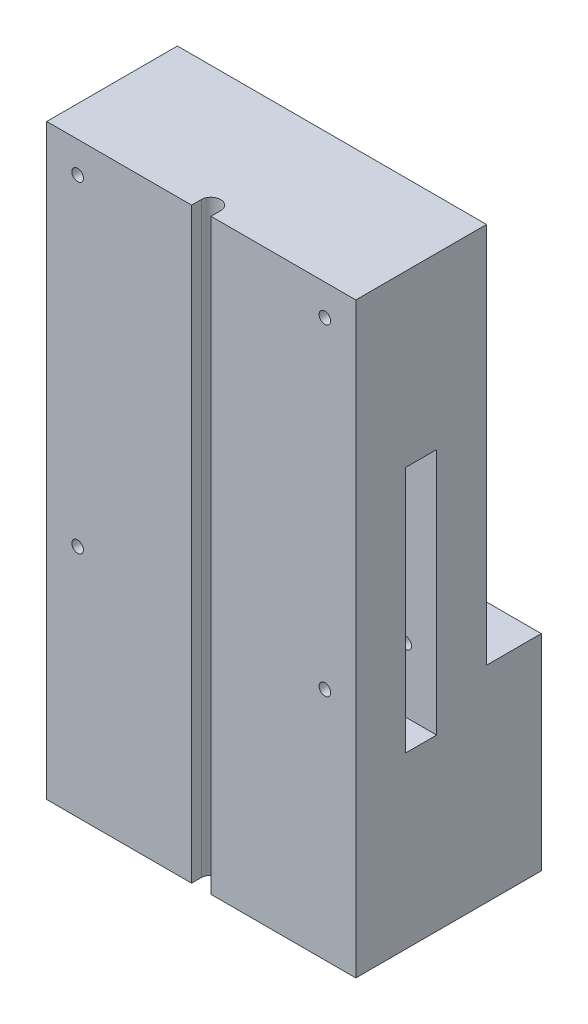
SolidWorks part; units mm, degrees
ref_plane "Front Plane" through (0, 0, 0) normal (0, 0, 1) x (1, 0, 0)
ref_plane "Top Plane" through (0, 0, 0) normal (0, 1, 0) x (1, 0, 0)
ref_plane "Right Plane" through (0, 0, 0) normal (1, 0, 0) x (0, 0, -1)
sketch "Sketch1" plane through (0, 0, 0) normal (0, 0, 1) x (1, 0, 0)
  line L1 (63.5, -120.65) -> (-63.5, -120.65)
  line L2 (63.5, -120.65) -> (63.5, 120.65)
  line L3 (63.5, 120.65) -> (-63.5, 120.65)
  line L4 (-63.5, -120.65) -> (-63.5, 120.65)
  line L5 (63.5, -120.65) -> (-63.5, 120.65) construction
  line L6 (63.5, 120.65) -> (-63.5, -120.65) construction
  point P0 (0, 0)
  dimension "D1" = 241.3
  dimension "D2" = 127
extrude "Boss-Extrude1" add sketch "Sketch1" along normal mid plane 76.2
sketch "Sketch2" plane through (0, 120.65, 0) normal (0, 1, 0) x (1, 0, 0)
  line L0 (-3.9688, -38.1) -> (-3.9688, -34.1313)
  line L1 (63.5, -38.1) -> (-63.5, -38.1) construction
  line L2 (3.9688, -38.1) -> (3.9688, -34.1313)
  line L3 (-3.9688, -34.1313) -> (0, -34.1313) construction
  line L4 (-3.9688, -38.1) -> (3.9688, -38.1)
  arc A0 (-3.9688, -34.1313) -> (3.9688, -34.1313) centre (0, -34.1313) cw
  dimension "D1" = 7.9375
extrude "Cut-Extrude1" cut sketch "Sketch2" against normal up to next contours A0 L2 L4 L0
sketch "Sketch3" plane through (0, 0, -38.1) normal (0, 0, -1) x (-1, 0, 0)
  line L0 (-22.9598, 76.2) -> (-35.7091, 76.2) construction
  line L2 (2.3909, 76.2) -> (-16.5941, 76.2) construction
  line L3 (2.3909, 31.75) -> (2.3909, 76.2) construction
  line L4 (-0.7841, 3.81) -> (-0.7841, 31.75) construction
  line L5 (-15.2621, 3.81) -> (-15.2621, 31.75) construction
  line L6 (-25.5491, 3.81) -> (-25.5491, 31.75) construction
  line L7 (-35.7091, 3.81) -> (-35.7091, 31.75) construction
  line L8 (-35.7091, 39.878) -> (-35.7091, 31.75) construction
  line L9 (-0.7841, 3.81) -> (-15.2621, 3.81) construction
  line L10 (-25.5491, 3.81) -> (-35.7091, 3.81) construction
  line L11 (-35.7091, 31.75) -> (2.3909, 31.75) construction
  line L12 (-35.7091, 76.2) -> (-35.7091, 57.8612) construction
  line L13 (-35.7091, 57.8612) -> (-35.7091, 39.878) construction
  line L14 (-23.7711, 94.234) -> (-23.7711, 76.2) construction
  line L15 (-15.7828, 76.2) -> (-15.7828, 94.234) construction
  line L16 (-42.7769, 94.234) -> (12.2231, 94.234) construction
  line L17 (21.4409, 3.81) -> (21.4409, 81.026) construction
  line L18 (21.4409, 81.026) -> (42.7769, 81.026) construction
  line L19 (42.7769, 3.81) -> (42.7769, 81.026) construction
  line L20 (21.4409, 3.81) -> (42.7769, 3.81) construction
  line L21 (-23.7711, 76.2) -> (-35.7091, 76.2) construction
  line L22 (-37.6141, 78.105) -> (-37.6141, 57.8612)
  line L23 (2.3909, 76.2) -> (-15.7828, 76.2) construction
  line L24 (2.3909, 31.75) -> (2.3909, 76.2) construction
  line L25 (-0.7841, 3.81) -> (-0.7841, 31.75) construction
  line L26 (-15.2621, 3.81) -> (-15.2621, 31.75) construction
  line L27 (-25.5491, 3.81) -> (-25.5491, 31.75) construction
  line L28 (-35.7091, 3.81) -> (-35.7091, 31.75) construction
  line L29 (-35.7091, 39.878) -> (-35.7091, 31.75) construction
  line L30 (-0.7841, 3.81) -> (-15.2621, 3.81) construction
  line L31 (-25.5491, 3.81) -> (-35.7091, 3.81) construction
  line L32 (-25.5491, 31.75) -> (-15.2621, 31.75) construction
  line L33 (-35.7091, 76.2) -> (-35.7091, 57.8612) construction
  line L34 (-35.7091, 57.8612) -> (-35.7091, 39.878) construction
  line L35 (-23.7711, 94.234) -> (-23.7711, 76.2) construction
  line L36 (-15.7828, 76.2) -> (-15.7828, 94.234) construction
  line L37 (-23.7711, 94.234) -> (-15.7828, 94.234) construction
  line L38 (21.4409, 3.81) -> (21.4409, 81.026) construction
  line L39 (21.4409, 81.026) -> (42.7769, 81.026) construction
  line L40 (42.7769, 3.81) -> (42.7769, 81.026) construction
  line L41 (21.4409, 3.81) -> (42.7769, 3.81) construction
  line L42 (-0.7841, 31.75) -> (2.3909, 31.75) construction
  line L43 (-37.6141, 57.8612) -> (-37.6141, 39.878)
  line L44 (-37.6141, 39.878) -> (-37.6141, 31.75)
  line L45 (-37.6141, 1.905) -> (-37.6141, 31.75)
  line L46 (-23.6441, 1.905) -> (-37.6141, 1.905)
  line L47 (-23.6441, 1.905) -> (-23.6441, 29.845)
  line L48 (-23.6441, 29.845) -> (-17.1671, 29.845)
  line L49 (-17.1671, 1.905) -> (-17.1671, 29.845)
  line L50 (1.1209, 1.905) -> (-17.1671, 1.905)
  line L51 (1.1209, 1.905) -> (1.1209, 29.845)
  line L52 (1.1209, 29.845) -> (4.2959, 29.845)
  line L53 (4.2959, 29.845) -> (4.2959, 78.105)
  line L54 (4.2959, 78.105) -> (-13.8778, 78.105)
  line L55 (-13.8778, 78.105) -> (-13.8778, 96.139)
  line L56 (-25.6761, 96.139) -> (-13.8778, 96.139)
  line L57 (-25.6761, 96.139) -> (-25.6761, 78.105)
  line L58 (19.5359, 1.905) -> (19.5359, 82.931)
  line L59 (19.5359, 82.931) -> (44.6819, 82.931)
  line L60 (44.6819, 1.905) -> (44.6819, 82.931)
  line L61 (19.5359, 1.905) -> (44.6819, 1.905)
  line L62 (-25.6761, 78.105) -> (-37.6141, 78.105)
  line L63 (-22.9598, 78.105) -> (-37.6141, 78.105) construction
  line L64 (-25.6761, 96.139) -> (-25.6761, 76.2) construction
  line L65 (4.2959, 78.105) -> (-16.5941, 78.105) construction
  line L66 (-13.8778, 76.2) -> (-13.8778, 96.139) construction
  line L67 (-22.9598, 76.2) -> (-35.7091, 76.2) construction
  line L68 (2.3909, 76.2) -> (-16.5941, 76.2) construction
  dimension "D1" = 1.905
extrude "Cut-Extrude2" cut sketch "Sketch3" against normal up to vertex (37.5875 mm away)
sketch "Sketch4" plane through (0, 0, -38.1) normal (0, 0, -1) x (-1, 0, 0)
  line L0 (12.8581, 102.235) -> (-43.4119, 102.235)
  line L1 (-43.4119, 102.235) -> (-43.4119, 93.599)
  line L2 (-43.4119, 93.599) -> (12.8581, 93.599)
  line L3 (12.8581, 93.599) -> (12.8581, 102.235)
  line L4 (-42.7769, 94.234) -> (12.2231, 94.234)
  line L5 (12.2231, 94.234) -> (12.2231, 101.6)
  line L6 (12.2231, 101.6) -> (-42.7769, 101.6)
  line L7 (-42.7769, 101.6) -> (-42.7769, 94.234)
  line L8 (-42.7769, 94.234) -> (12.2231, 94.234) construction
  line L9 (12.2231, 94.234) -> (12.2231, 101.6) construction
  line L10 (12.2231, 101.6) -> (-42.7769, 101.6) construction
  line L11 (-42.7769, 101.6) -> (-42.7769, 94.234) construction
  dimension "D1" = 0
  dimension "D2" = 0.635
extrude "Cut-Extrude3" cut sketch "Sketch4" against normal up to vertex (61.9125 mm away)
sketch "Sketch5" plane through (0, 0, -38.1) normal (0, 0, -1) x (-1, 0, 0)
  line L1 (-63.5, 120.65) -> (63.5, 120.65)
  line L2 (-63.5, 120.65) -> (-63.5, -36.195)
  line L3 (-63.5, -36.195) -> (63.5, -36.195)
  line L4 (63.5, 120.65) -> (63.5, -36.195)
  line L8 (19.5359, 1.905) -> (44.6819, 1.905) construction
  dimension "D1" = 38.1
extrude "Cut-Extrude4" cut sketch "Sketch5" against normal blind 22.4917
sketch "Sketch6" plane through (0, 0, -15.6083) normal (0, 0, -1) x (-1, 0, 0)
  line L1 (-63.5, -36.195) -> (63.5, -36.195) construction
  line L4 (-50.8, -24.2888) -> (-50.8, 107.95) construction
  line L5 (50.8, 107.95) -> (50.8, -24.2888) construction
  line L6 (50.8, -24.2888) -> (-50.8, -24.2888) construction
  line L7 (-50.8, 107.95) -> (50.8, 107.95) construction
  line L9 (63.5, 120.65) -> (-63.5, 120.65) construction
  line L10 (63.5, -36.195) -> (63.5, 120.65) construction
  line L11 (-63.5, 120.65) -> (-63.5, -36.195) construction
  circle A0 centre (-50.8, -24.2888) radius 2.3812
  circle A1 centre (50.8, 107.95) radius 2.3812
  circle A2 centre (50.8, -24.2888) radius 2.3812
  circle A3 centre (-50.8, 107.95) radius 2.3812
  point P8 (-50.8, -26.67)
  point P9 (-53.1812, -24.2888)
  point P10 (50.8, 110.3313)
  point P11 (53.1813, 107.95)
  dimension "D5" = 4.7625
  dimension "D1" = 12.7
  dimension "D2" = 9.525
  dimension "D3" = 12.7
  dimension "D4" = 12.7
extrude "Cut-Extrude5" cut sketch "Sketch6" against normal up to next
sketch "Sketch7" plane through (63.5, 0, 0) normal (1, 0, 0) x (0, 0, -1)
  line L0 (0, 0) -> (-11.2458, 0) construction
  line L1 (-4.8958, -50.8) -> (-17.5958, -50.8)
  line L2 (-4.8958, -50.8) -> (-4.8958, 50.8)
  line L3 (-4.8958, 50.8) -> (-17.5958, 50.8)
  line L4 (-17.5958, -50.8) -> (-17.5958, 50.8)
  line L5 (-4.8958, -50.8) -> (-17.5958, 50.8) construction
  line L6 (-4.8958, 50.8) -> (-17.5958, -50.8) construction
  line L7 (-11.2459, 120.65) -> (-11.2458, 0) construction
  line L8 (-38.1, 120.65) -> (15.6083, 120.65) construction
  point P0 (-11.2458, 0)
  dimension "D1" = 12.7
  dimension "D2" = 101.6
extrude "Cut-Extrude6" cut sketch "Sketch7" against normal blind 12.7
